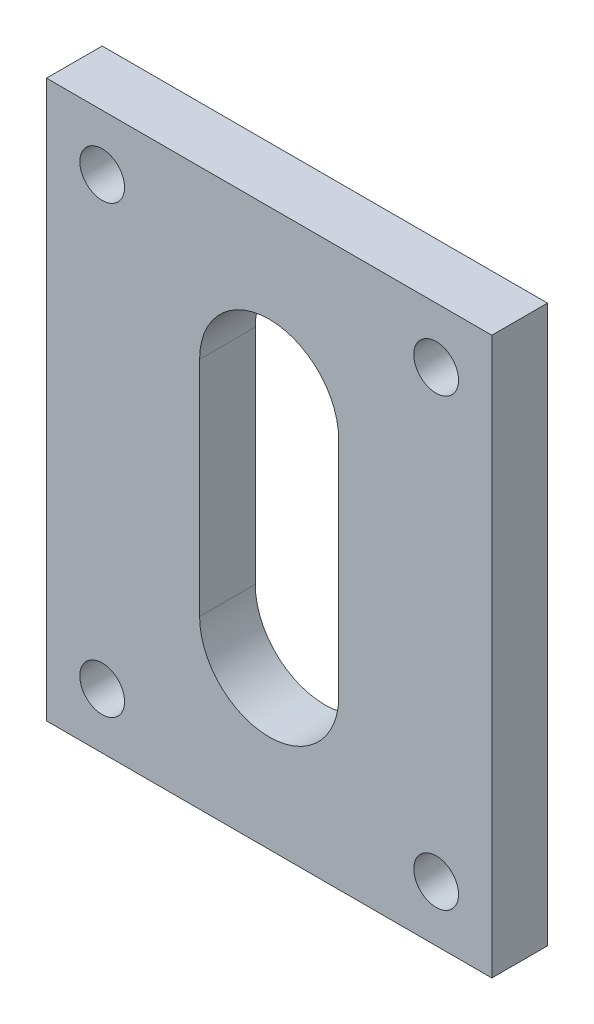
SolidWorks part; units mm, degrees
ref_plane "Front Plane" through (0, 0, 0) normal (0, 0, 1) x (1, 0, 0)
ref_plane "Top Plane" through (0, 0, 0) normal (0, 1, 0) x (1, 0, 0)
ref_plane "Right Plane" through (0, 0, 0) normal (1, 0, 0) x (0, 0, -1)
sketch "Sketch1" plane through (0, 0, 0) normal (0, 0, 1) x (1, 0, 0)
  line L0 (0, 31.75) -> (0, -31.75) construction
  line L1 (-25.4, -31.75) -> (25.4, -31.75)
  line L2 (-25.4, -31.75) -> (-25.4, 31.75)
  line L3 (-25.4, 31.75) -> (25.4, 31.75)
  line L4 (25.4, -31.75) -> (25.4, 31.75)
  line L5 (-25.4, -31.75) -> (25.4, 31.75) construction
  line L6 (-25.4, 31.75) -> (25.4, -31.75) construction
  line L7 (25.4, 0) -> (-25.4, 0) construction
  line L8 (0, -12.7) -> (0, 12.7) construction
  line L9 (-7.9375, -12.7) -> (-7.9375, 12.7)
  line L10 (7.9375, -12.7) -> (7.9375, 12.7)
  circle A0 centre (-19.05, 25.4) radius 2.5527
  circle A1 centre (19.05, 25.4) radius 2.5527
  circle A2 centre (19.05, -25.4) radius 2.5527
  circle A3 centre (-19.05, -25.4) radius 2.5527
  arc A4 (-7.9375, -12.7) -> (7.9375, -12.7) centre (0, -12.7) ccw
  arc A5 (7.9375, 12.7) -> (-7.9375, 12.7) centre (0, 12.7) ccw
  point P0 (0, 0)
  point P20 (0, 0)
  dimension "D3" = 5.1054
  dimension "D1" = 50.8
  dimension "D2" = 63.5
  dimension "D4" = 19.05
  dimension "D5" = 25.4
  dimension "D6" = 15.875
  dimension "D7" = 25.4
extrude "Boss-Extrude1" add sketch "Sketch1" along normal blind 6.35
